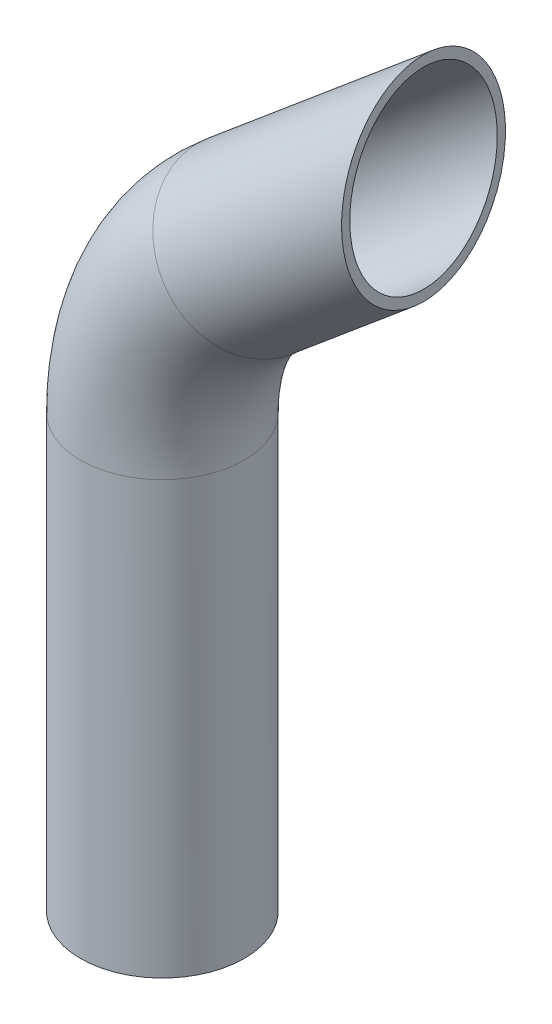
SolidWorks part; units mm, degrees
ref_plane "Front Plane" through (0, 0, 0) normal (0, 0, 1) x (1, 0, 0)
ref_plane "Top Plane" through (0, 0, 0) normal (0, 1, 0) x (1, 0, 0)
ref_plane "Right Plane" through (0, 0, 0) normal (1, 0, 0) x (0, 0, -1)
sketch "Sketch1" plane through (0, 0, 0) normal (0, 0, 1) x (1, 0, 0)
  line L0 (0, -144.4793) -> (0, 13.553)
  line L1 (32.1491, 82.497) -> (114.9067, 151.9388)
  arc A0 (0, 13.553) -> (32.1491, 82.497) centre (90, 13.553) cw
  point P6 (0, 55.5207)
  dimension "D4" = 90
  dimension "D1" = 130
  dimension "D2" = 150
  dimension "D3" = 200
ref_plane "Plane1" through (114.9067, 151.9388, 0) normal (-0.766, -0.6428, 0) x (0, 0, 1)
sketch "Sketch2" plane through (114.9067, 151.9388, 0) normal (-0.766, -0.6428, 0) x (0, 0, 1)
  circle A0 centre (0, 0) radius 30
  dimension "D1" = 60
sweep "Sweep-Thin1" add profiles "Sketch2" path "Sketch1" parameters "D1"=3
sketch "Sketch4" plane through (0, 0, 0) normal (0, 0, 1) x (1, 0, 0)
  line L0 (95.623, 174.9201) -> (95.623, 96.5957)
  line L1 (95.623, 174.9201) -> (134.1903, 128.9575)
  line L2 (134.1903, 128.9575) -> (95.623, 96.5957)
  line L3 (51.4327, 59.5156) -> (134.1903, 128.9575) construction
  line L4 (30, -144.4793) -> (30, 13.553) construction
extrude "Cut-Extrude1" cut sketch "Sketch4" against normal mid plane 80
